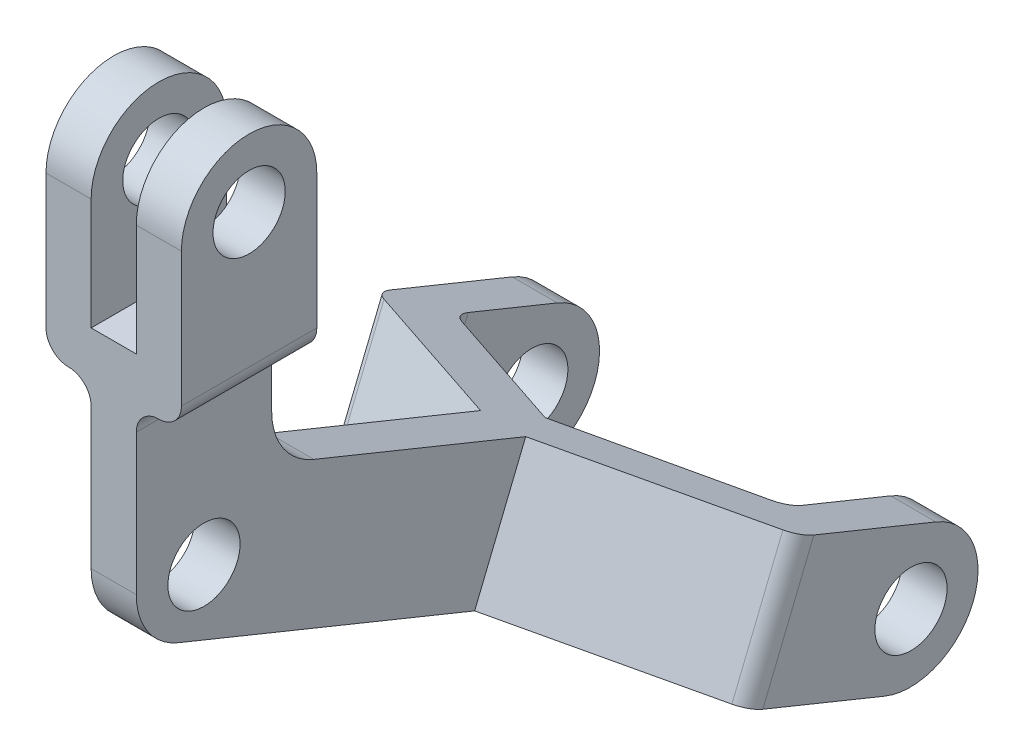
SolidWorks part; units mm, degrees
ref_plane "Front Plane" through (0, 0, 0) normal (0, 0, 1) x (1, 0, 0)
ref_plane "Top Plane" through (0, 0, 0) normal (0, 1, 0) x (1, 0, 0)
ref_plane "Right Plane" through (0, 0, 0) normal (1, 0, 0) x (0, 0, -1)
sketch "Sketch1" plane through (0, 0, 0) normal (1, 0, 0) x (0, 0, -1)
  line L0 (0, 0) -> (15, 0)
  line L2 (0, 0) -> (0, -15.9)
  line L3 (0, -15.9) -> (0, -15.59)
  line L4 (4.6728, -22.5367) -> (37.4848, -35.8904)
  line L5 (37.4848, -35.8904) -> (43.1391, -21.997)
  line L6 (43.1391, -21.997) -> (19.6728, -12.4467)
  line L8 (15, 0) -> (15, -5.5)
  arc A0 (0, -15.59) -> (4.6728, -22.5367) centre (7.5, -15.59) ccw
  arc A1 (19.6728, -12.4467) -> (15, -5.5) centre (22.5, -5.5) cw
  circle A2 centre (7.5, -16.4624) radius 4
  dimension "D3" = 7.5
  dimension "D4" = 7.5
  dimension "D9" = 8
  dimension "D1" = 15
  dimension "D2" = 15
  dimension "D5" = 5.5
  dimension "D6" = 15.59
  dimension "D7" = 6.7
  dimension "D8" = 7.5
extrude "Boss-Extrude1" add sketch "Sketch1" along normal blind 5 contours L6 A1 L8 L0 L2 A0 L4 L5 A2
sketch "Sketch2" plane through (0, 0, 0) normal (0, 0, 1) x (1, 0, 0)
  line L0 (0, 0) -> (5, 0)
  line L1 (5, 0) -> (5, -15.59) construction
  line L2 (10, 5) -> (10, 19.86)
  line L3 (10, 19.86) -> (5, 19.86)
  line L4 (5, 19.86) -> (5, 7.5)
  line L5 (5, 7.5) -> (0, 7.5)
  line L6 (0, 19.86) -> (0, 7.5)
  line L7 (2.5, 0) -> (2.5, 22.7767) construction
  line L8 (-5, 19.86) -> (0, 19.86)
  line L9 (-5, 5) -> (-5, 19.86)
  arc A0 (5, 0) -> (7.5, 2.5) centre (7.5, 0) cw
  arc A1 (7.5, 2.5) -> (10, 5) centre (7.5, 5) ccw
  arc A2 (-2.5, 2.5) -> (-5, 5) centre (-2.5, 5) cw
  arc A3 (0, 0) -> (-2.5, 2.5) centre (-2.5, 0) ccw
  point P22 (2.5, 7.5)
  dimension "D4" = 2.5
  dimension "D5" = 2.5
  dimension "D1" = 2.5
  dimension "D2" = 5
  dimension "D3" = 14.86
  dimension "D6" = 12.36
extrude "Boss-Extrude2" add sketch "Sketch2" against normal up to surface (15 mm away) up to face at (2.5, -2.75, -15)
sketch "Sketch3" plane through (10, 0, 0) normal (1, 0, 0) x (0, 0, -1)
  line L0 (0, 19.86) -> (27.8005, 19.86) construction
  line L2 (7.5, 5) -> (7.5, 19.86) construction
  line L3 (15, 5) -> (0, 5) construction
  circle A0 centre (7.5, 19.86) radius 7.5
  circle A1 centre (7.5, 19.86) radius 4
  dimension "D1" = 8
extrude "Boss-Extrude3" add sketch "Sketch3" against normal up to surface (5 mm away) up to face at (5, 13.68, -7.5)
sketch "Sketch5" plane through (10, 0, 0) normal (1, 0, 0) x (0, 0, -1)
  line L0 (11.5, 19.86) -> (3.5, 19.86) construction
  circle A0 centre (7.5, 19.86) radius 4
extrude "Cut-Extrude1" cut sketch "Sketch5" against normal blind 5
sketch "Sketch6" plane through (-5, 0, 0) normal (-1, 0, 0) x (0, 0, 1)
  line L0 (-15, 19.86) -> (0, 19.86) construction
  circle A0 centre (-7.5, 19.86) radius 7.5
extrude "Boss-Extrude4" add sketch "Sketch6" against normal up to surface (5 mm away) up to face at (0, 13.68, -7.5)
sketch "Sketch7" plane through (-5, 0, 0) normal (-1, 0, 0) x (0, 0, 1)
  circle A0 centre (-7.5, 19.86) radius 4
extrude "Cut-Extrude2" cut sketch "Sketch7" against normal blind 5
sketch "Sketch8" plane through (0, -3.8094, 1.5503) normal (0, 0.9262, -0.377) x (1, 0, 0)
  line L0 (0, 48.2487) -> (5, 48.2487)
  line L2 (0, 48.2487) -> (-19.6852, 57.9592)
  line L3 (-21.0793, 60.2013) -> (-21.0793, 74.7913)
  line L4 (-21.0793, 74.7913) -> (-16.0793, 74.7913)
  line L5 (-16.0793, 74.7913) -> (-16.0793, 64.1288)
  line L6 (-14.6852, 61.8867) -> (2.2583, 53.5287)
  line L7 (19.5563, 61.9014) -> (2.2583, 53.5287)
  line L8 (20.9211, 74.713) -> (20.9211, 64.1288)
  line L9 (25.9211, 74.713) -> (20.9211, 74.713)
  line L10 (25.9211, 60.123) -> (25.9211, 74.713)
  line L11 (5, 48.2487) -> (24.5563, 57.8956)
  arc A0 (-19.6852, 57.9592) -> (-21.0793, 60.2013) centre (-18.5793, 60.2013) cw
  arc A1 (-16.0793, 64.1288) -> (-14.6852, 61.8867) centre (-13.5793, 64.1288) ccw
  arc A2 (20.9211, 64.1288) -> (19.5563, 61.9014) centre (18.4211, 64.1288) cw
  arc A3 (24.5563, 57.8956) -> (25.9211, 60.123) centre (23.4211, 60.123) ccw
  dimension "D4" = 2.5
  dimension "D5" = 2.5
  dimension "D1" = 5
  dimension "D2" = 14.59
  dimension "D3" = 21.95
  dimension "D6" = 5.28
extrude "Boss-Extrude5" add sketch "Sketch8" against normal up to surface (15 mm away) up to face at (2.5, -29.2136, -21.0788)
sketch "Sketch9" plane through (25.9211, 0, 0) normal (1, 0, 0) x (0, 0, -1)
  line L0 (61.9969, -45.8663) -> (67.6512, -31.9728) construction
  circle A0 centre (64.824, -38.9196) radius 7.5
extrude "Boss-Extrude6" add sketch "Sketch9" against normal up to surface (5 mm away) up to face at (20.9211, -36.9247, -59.9223)
sketch "Sketch10" plane through (-21.0793, 0, 0) normal (-1, 0, 0) x (0, 0, 1)
  line L0 (-62.0694, -45.8958) -> (-67.7237, -32.0023) construction
  circle A0 centre (-64.8965, -38.9491) radius 7.5
extrude "Boss-Extrude7" add sketch "Sketch10" against normal up to surface (5 mm away) up to face at (-16.0793, -36.9394, -59.9586)
sketch "Sketch11" plane through (25.9211, 0, 0) normal (1, 0, 0) x (0, 0, -1)
  circle A0 centre (64.8965, -38.9491) radius 4
  dimension "D1" = 8
extrude "Cut-Extrude3" cut sketch "Sketch11" against normal blind 64
scale "Scale1" scale about centroid uniform scaling yes scale factor 0.7
